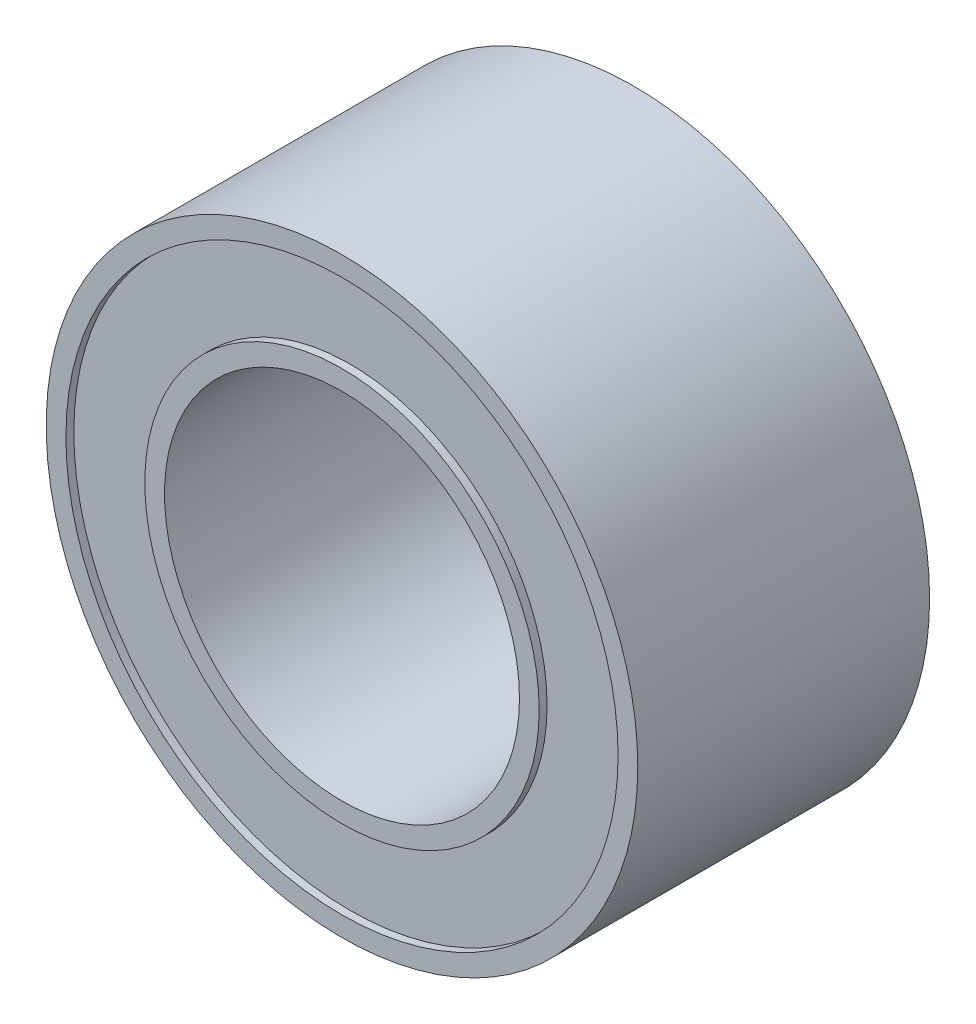
SolidWorks part; units mm, degrees
ref_plane "Płaszczyzna przednia" through (0, 0, 0) normal (0, 0, 1) x (1, 0, 0)
ref_plane "Płaszczyzna górna" through (0, 0, 0) normal (0, 1, 0) x (1, 0, 0)
ref_plane "Płaszczyzna prawa" through (0, 0, 0) normal (1, 0, 0) x (0, 0, -1)
sketch "Szkic1" plane through (0, 0, 0) normal (0, 0, 1) x (1, 0, 0)
  circle A0 centre (0, 0) radius 22.5
  circle A1 centre (0, 0) radius 37.5
  dimension "D1" = 75
  dimension "D2" = 45
extrude "Dodanie-wyciągnięcie1" add sketch "Szkic1" along normal blind 37
sketch "Szkic2" plane through (0, 0, 37) normal (0, 0, 1) x (1, 0, 0)
  circle A0 centre (0, 0) radius 25
  circle A1 centre (0, 0) radius 35
  dimension "D1" = 70
  dimension "D2" = 50
extrude "Wytnij-wyciągnięcie1" cut sketch "Szkic2" against normal blind 1
ref_plane "Płaszczyzna1" through (0, 0, 18.5) normal (0, 0, 1) x (1, 0, 0)
mirror "Lustro1" about plane through (0, 0, 18.5) normal (0, 0, 1) of "Wytnij-wyciągnięcie1"
